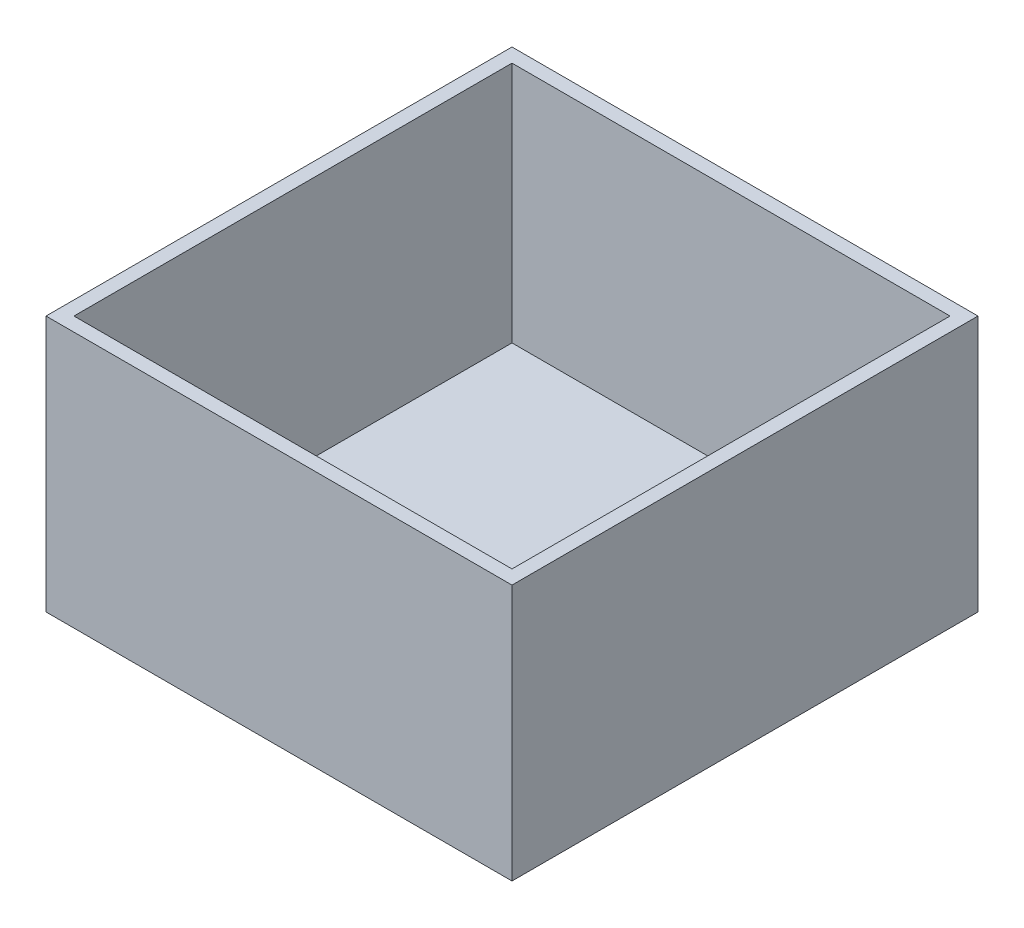
SolidWorks part; units mm, degrees
ref_plane "前视基准面" through (0, 0, 0) normal (0, 0, 1) x (1, 0, 0)
ref_plane "上视基准面" through (0, 0, 0) normal (0, 1, 0) x (1, 0, 0)
ref_plane "右视基准面" through (0, 0, 0) normal (1, 0, 0) x (0, 0, -1)
other "Configuration Table"
sketch "草图1" plane through (0, 0, 0) normal (0, 0, 1) x (1, 0, 0)
  line L1 (0, 0) -> (20, 0)
  line L2 (0, 0) -> (0, 20)
  line L3 (0, 20) -> (20, 20)
  line L4 (20, 0) -> (20, 20)
extrude "凸台-拉伸1" add sketch "草图1" along normal blind 120 contours L2 L1 L4 L3
sketch "草图2" plane through (0, 20, 0) normal (0, 1, 0) x (1, 0, 0)
  line L1 (20, 0) -> (10, 0)
  line L2 (20, 0) -> (20, -20)
  line L3 (20, -20) -> (10, -20)
  line L4 (10, 0) -> (10, -20)
extrude "切除-拉伸1" cut sketch "草图2" against normal blind 120
sketch "草图3" plane through (10, 0, 0) normal (1, 0, 0) x (0, 0, -1)
  line L0 (-20, 20) -> (0, 0)
  circle A0 centre (-10, 10) radius 1.55
extrude "切除-拉伸2" cut sketch "草图3" against normal blind 120 contours L0 A0 | L0 A0
sketch "草图4" plane through (0, 0, 0) normal (-1, 0, 0) x (0, 0, 1)
  circle A0 centre (10, 10) radius 3
extrude "切除-拉伸3" cut sketch "草图4" against normal blind 2
sketch "草图8" plane through (0, 0, 120) normal (0, 0, 1) x (1, 0, 0)
  line L0 (0, 20) -> (0.2, 20)
  line L1 (0, 20) -> (20, 20) construction
  line L2 (0, 20) -> (0, 19.8)
  line L3 (0, 0) -> (0, 20) construction
  line L4 (0, 19.8) -> (20, 19.8)
  line L5 (20, 0) -> (20, 20) construction
  line L6 (0.2, 20) -> (0.2, 19.8)
  line L7 (0.2, 19.8) -> (0.2, 0)
  line L8 (0, 0) -> (20, 0) construction
  line L9 (0.2, 0) -> (0, 0)
  line L10 (0, 0) -> (0, 0.2)
  line L11 (0, 0.2) -> (20, 0.2)
  line L12 (20, 0.2) -> (20, 0)
  line L13 (20, 0) -> (19.8, 0)
  line L14 (19.8, 0) -> (19.8, 20)
  line L15 (19.8, 20) -> (20, 20)
  line L16 (20, 20) -> (20, 0.2)
  line L17 (19.8, 0) -> (0.2, 0)
  line L18 (0.2, 0) -> (19.8, 0)
  line L19 (0, 0.2) -> (0.2, 0.2)
  line L20 (0.2, 0.2) -> (0.2, 0)
  line L21 (0, 0.2) -> (0, 19.8)
  line L22 (0.2, 20) -> (19.8, 20)
  line L23 (19.8, 20) -> (19.8, 19.8)
  line L24 (19.8, 19.8) -> (20, 19.8)
  line M5 (20, 20) -> (0, 20)
  line M6 (0, 20) -> (0, 0)
  line M7 (0, 0) -> (20, 0)
  line M8 (20, 0) -> (20, 20)
extrude "切除-拉伸6" cut sketch "草图8" against normal blind 15 contours L4 L14 L6 M5 | L6 L4 M5 M6 | L11 L7 L4 M6 | L14 L11 L4 M8 | L14 L11 M7 M8 | L14 L11 L7 M7 | L11 L7 M6 M7 | L14 L4 M8 M5
sketch "草图9" plane through (0, 20, 0) normal (0, 1, 0) x (1, 0, 0)
  line L0 (0, -105) -> (0, -45)
  line L1 (0, -105) -> (0, 0) construction
  line L3 (0, -45) -> (20, -45)
  line L4 (0, -45) -> (0, 0)
  line L5 (0, 0) -> (20, 0)
  line L6 (20, -45) -> (20, 0)
  line M6 (0, 0) -> (0, -105)
  line M8 (20, -105) -> (20, -20)
  line M9 (20, -20) -> (10, -20)
  line M10 (10, -20) -> (10, 0)
  line M11 (10, 0) -> (0, 0)
extrude "切除-拉伸7" cut sketch "草图9" against normal blind 20 contours L3 M6 M8 M9 M10 M11 | L6 L5 M9 M10
sketch "草图10" plane through (0, 0, 45) normal (0, 0, -1) x (-1, 0, 0)
  line L0 (-20, 0) -> (-19.8, 0)
  line L1 (0, 0) -> (-20, 0) construction
  line L2 (-19.8, 0) -> (-19.8, 0.2)
  line L6 (0, 20) -> (-0.2, 20)
  line L7 (0, 20) -> (-20, 20) construction
  line L8 (-0.2, 20) -> (-0.2, 19.8)
  line L9 (-19.8, 0.2) -> (-0.2, 0.2)
  line L10 (-19.8, 0.2) -> (-19.8, 19.8)
  line L11 (-19.8, 19.8) -> (-0.2, 19.8)
  line L12 (-0.2, 0.2) -> (-0.2, 19.8)
extrude "凸台-拉伸2" add sketch "草图10" along normal blind 15 contours L10 L9 L12 L11
sketch "草图11" plane through (0, 19.8, 0) normal (0, 1, 0) x (1, 0, 0)
  line L0 (0, -105) -> (0, -120)
  line L1 (0, -120) -> (19.9951, -120)
  line L2 (19.9951, -120) -> (20, -105)
  line L3 (20, -105) -> (0, -105)
  line L4 (0, -105) -> (19.9951, -120)
  circle A0 centre (9.9976, -112.5) radius 1.55
extrude "切除-拉伸8" cut sketch "草图11" against normal blind 20 contours L4 A0 | L4 A0
sketch "草图12" plane through (0, 19.8, 0) normal (0, 1, 0) x (1, 0, 0)
  line L0 (0, -45) -> (0, -30)
  line L1 (0, -30) -> (20, -30)
  line L2 (20, -30) -> (20, -45)
  line L3 (20, -45) -> (0, -30)
  circle A0 centre (10, -37.5) radius 1.55
extrude "切除-拉伸9" cut sketch "草图12" against normal blind 20 contours L3 A0 | L3 A0
sketch "草图13" plane through (0, 0, 0) normal (-1, 0, 0) x (0, 0, 1)
  line L0 (105, 20) -> (45, 20) construction
  line L1 (45, 0) -> (50, 0)
  line L2 (45, 0) -> (45, 20)
  line L3 (45, 20) -> (50, 20)
  line L4 (50, 0) -> (50, 20)
  line L6 (50, 0) -> (123.8282, 0)
  line L7 (50, 0) -> (50, 20)
  line L8 (50, 20) -> (123.8282, 20)
  line L9 (123.8282, 0) -> (123.8282, 20)
  line M10 (45, 0) -> (105, 0)
  line M11 (105, 0) -> (105, 20)
  line M12 (105, 20) -> (45, 20)
extrude "切除-拉伸10" cut sketch "草图13" against normal blind 20 contours L4 M10 M11 M12 | L6 L9 L8 M11
sketch "草图14" plane through (0, 0, 50) normal (0, 0, 1) x (1, 0, 0)
  line L0 (0, 20) -> (20, 0)
  line L1 (20, 0) -> (20, 20) construction
  line L2 (20, 0) -> (0, 0) construction
  line L3 (10, 10) -> (60, 10)
  line L4 (10, 10) -> (10, 45)
  line L5 (10, 10) -> (-40, 10)
  line L6 (10, 10) -> (10, -10)
  line L9 (-40, 10) -> (-40, -10)
  line L10 (60, 10) -> (60, 45)
  line L14 (-40, -10) -> (60, -10)
  line L15 (-40, -10) -> (-40, 45)
  line L16 (-40, 45) -> (60, 45)
  line L17 (60, -10) -> (60, 45)
extrude "凸台-拉伸5" add sketch "草图14" against normal blind 5 contours L15 L14 L17 L16
sketch "草图17" plane through (-40, 0, 0) normal (-1, 0, 0) x (0, 0, 1)
  line L0 (45, -10) -> (50, -10) construction
  line L1 (50, 45) -> (48, 45)
  line L2 (50, 45) -> (50, -10)
  line L3 (50, -10) -> (48, -10)
  line L4 (48, 45) -> (48, -10)
extrude "切除-拉伸12" cut sketch "草图17" against normal blind 1000
sketch "草图18" plane through (0, 0, 48) normal (0, 0, 1) x (1, 0, 0)
  line L0 (60, -10) -> (60, 45) construction
  line L1 (-40, -10) -> (60, -10)
  line L2 (-40, -10) -> (-40, -7)
  line L3 (-40, -7) -> (60, -7)
  line L4 (60, -10) -> (60, -7)
  line L6 (-40, 45) -> (-37, 45)
  line L7 (-40, 45) -> (-40, -10)
  line L8 (-40, -10) -> (-37, -10)
  line L9 (-37, 45) -> (-37, -10)
  line L10 (60, 45) -> (57, 45)
  line L11 (60, 45) -> (60, -10)
  line L12 (60, -10) -> (57, -10)
  line L13 (57, 45) -> (57, -10)
  line M6 (60, -10) -> (60, 45)
  line M7 (60, 45) -> (-40, 45)
  line M8 (-40, 45) -> (-40, -10)
  line M9 (-40, -10) -> (60, -10)
extrude "凸台-拉伸6" add sketch "草图18" along normal blind 94 contours L13 L3 M7 M6 | L13 L3 L9 L1 | L9 L3 M8 M9 | L3 L13 M9 M6
sketch "草图19" plane through (60, 0, 0) normal (1, 0, 0) x (0, 0, -1)
  line L1 (-142, -10) -> (-145, -10)
  line L2 (-142, -10) -> (-142, 45)
  line L3 (-142, 45) -> (-145, 45)
  line L4 (-145, -10) -> (-145, 45)
extrude "凸台-拉伸7" add sketch "草图19" against normal blind 100 contours L2 L1 L4 L3
